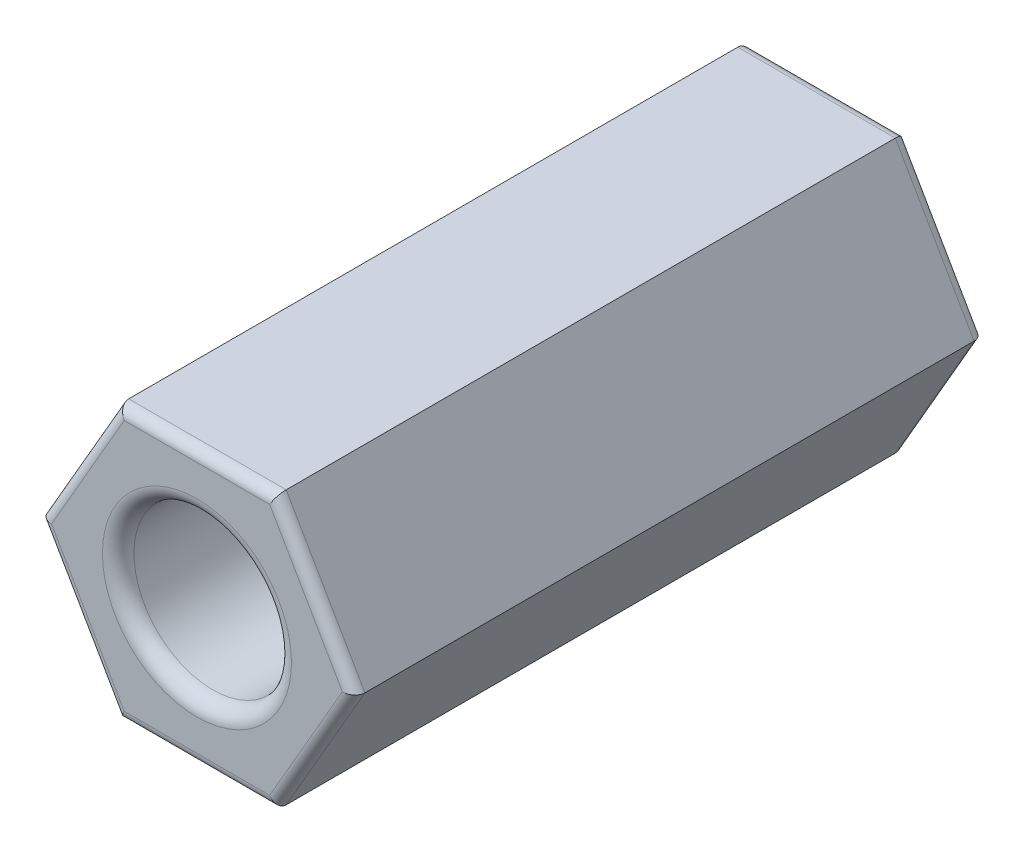
SolidWorks part; units mm, degrees
ref_plane "Front Plane" through (0, 0, 0) normal (0, 0, 1) x (1, 0, 0)
ref_plane "Top Plane" through (0, 0, 0) normal (0, 1, 0) x (1, 0, 0)
ref_plane "Right Plane" through (0, 0, 0) normal (1, 0, 0) x (0, 0, -1)
sketch "Sketch1" plane through (0, 0, 0) normal (0, 0, 1) x (1, 0, 0)
  line L1 (3, 0) -> (1.5, 2.5981)
  line L2 (1.5, 2.5981) -> (-1.5, 2.5981)
  line L3 (-1.5, 2.5981) -> (-3, 0)
  line L4 (-3, 0) -> (-1.5, -2.5981)
  line L5 (-1.5, -2.5981) -> (1.5, -2.5981)
  line L6 (1.5, -2.5981) -> (3, 0)
  circle A0 centre (0, 0) radius 2.5981 construction
  circle A1 centre (0, 0) radius 1.5
  dimension "D2" = 3
  dimension "D1" = 6
extrude "Boss-Extrude1" add sketch "Sketch1" along normal blind 12
fillet "Fillet1" radius 0.3 2 edges at (1.5, 0, 0) (1.5, 0, 12)
fillet "Fillet2" radius 0.2 12 edges at (-2.25, 1.299, 12) (-2.25, -1.299, 12) (0, -2.5981, 12) (2.25, -1.299, 12) (2.25, 1.299, 12) (0, 2.5981, 12) (2.25, -1.299, 0) (0, -2.5981, 0) (-2.25, -1.299, 0) (-2.25, 1.299, 0) (0, 2.5981, 0) (2.25, 1.299, 0)
sketch "Sketch2" plane through (0, 0, 0) normal (0, 0, 1) x (1, 0, 0)
  circle A0 centre (0, 0) radius 3 construction
